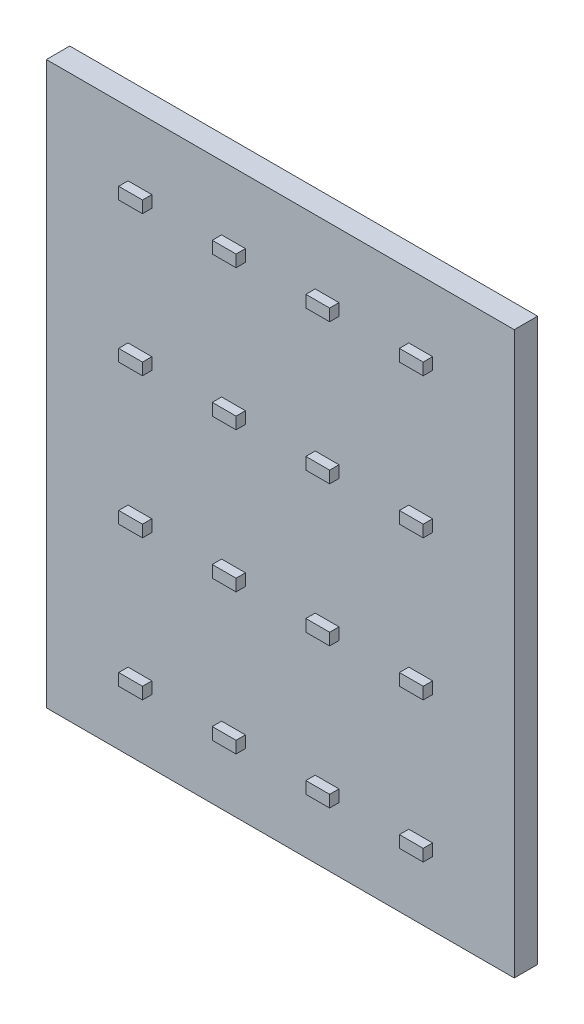
SolidWorks part; units mm, degrees
ref_plane "前视基准面" through (0, 0, 0) normal (0, 0, 1) x (1, 0, 0)
ref_plane "上视基准面" through (0, 0, 0) normal (0, 1, 0) x (1, 0, 0)
ref_plane "右视基准面" through (0, 0, 0) normal (1, 0, 0) x (0, 0, -1)
sketch "草图1" plane through (0, 0, 0) normal (0, 0, 1) x (1, 0, 0)
  line L1 (-50, 60) -> (50, 60)
  line L2 (-50, 60) -> (-50, -60)
  line L3 (-50, -60) -> (50, -60)
  line L4 (50, 60) -> (50, -60)
  line L5 (0, -60) -> (0, 60) construction
  line L6 (-50, 0) -> (50, 0) construction
  point P0 (0, 0)
  dimension "D1" = 120
  dimension "D2" = 100
extrude "凸台-拉伸1" add sketch "草图1" along normal blind 5
sketch "草图2" plane through (0, 0, 5) normal (0, 0, 1) x (1, 0, 0)
  line L0 (-12.543, 46.2715) -> (-12.543, 43.7285)
  line L1 (-32.543, 46.2715) -> (-27.457, 46.2715)
  line L2 (-32.543, 46.2715) -> (-32.543, 43.7285)
  line L3 (-32.543, 43.7285) -> (-27.457, 43.7285)
  line L4 (-27.457, 46.2715) -> (-27.457, 43.7285)
  line L5 (-30, 43.7285) -> (-30, 46.2715) construction
  line L6 (-32.543, 45) -> (-27.457, 45) construction
  line L11 (-12.543, 46.2715) -> (-7.457, 46.2715)
  line L12 (-7.457, 46.2715) -> (-7.457, 43.7285)
  line L17 (-12.543, 43.7285) -> (-7.457, 43.7285)
  line L18 (7.457, 46.2715) -> (7.457, 43.7285)
  line L19 (7.457, 46.2715) -> (12.543, 46.2715)
  line L20 (12.543, 46.2715) -> (12.543, 43.7285)
  line L21 (7.457, 43.7285) -> (12.543, 43.7285)
  line L22 (27.457, 46.2715) -> (27.457, 43.7285)
  line L23 (27.457, 46.2715) -> (32.543, 46.2715)
  line L24 (32.543, 46.2715) -> (32.543, 43.7285)
  line L25 (27.457, 43.7285) -> (32.543, 43.7285)
  line L26 (-32.543, 16.2715) -> (-32.543, 13.7285)
  line L27 (-32.543, 16.2715) -> (-27.457, 16.2715)
  line L28 (-27.457, 16.2715) -> (-27.457, 13.7285)
  line L29 (-32.543, 13.7285) -> (-27.457, 13.7285)
  line L30 (-12.543, 16.2715) -> (-12.543, 13.7285)
  line L31 (-12.543, 13.7285) -> (-7.457, 13.7285)
  line L32 (-7.457, 16.2715) -> (-7.457, 13.7285)
  line L33 (-12.543, 16.2715) -> (-7.457, 16.2715)
  line L34 (7.457, 16.2715) -> (7.457, 13.7285)
  line L35 (7.457, 13.7285) -> (12.543, 13.7285)
  line L36 (12.543, 16.2715) -> (12.543, 13.7285)
  line L37 (7.457, 16.2715) -> (12.543, 16.2715)
  line L38 (27.457, 16.2715) -> (27.457, 13.7285)
  line L39 (27.457, 13.7285) -> (32.543, 13.7285)
  line L40 (32.543, 16.2715) -> (32.543, 13.7285)
  line L41 (27.457, 16.2715) -> (32.543, 16.2715)
  line L42 (-32.543, -13.7285) -> (-32.543, -16.2715)
  line L43 (-32.543, -13.7285) -> (-27.457, -13.7285)
  line L44 (-27.457, -13.7285) -> (-27.457, -16.2715)
  line L45 (-32.543, -16.2715) -> (-27.457, -16.2715)
  line L46 (-12.543, -13.7285) -> (-12.543, -16.2715)
  line L47 (-12.543, -16.2715) -> (-7.457, -16.2715)
  line L48 (-7.457, -13.7285) -> (-7.457, -16.2715)
  line L49 (-12.543, -13.7285) -> (-7.457, -13.7285)
  line L50 (7.457, -13.7285) -> (7.457, -16.2715)
  line L51 (7.457, -16.2715) -> (12.543, -16.2715)
  line L52 (12.543, -13.7285) -> (12.543, -16.2715)
  line L53 (7.457, -13.7285) -> (12.543, -13.7285)
  line L54 (27.457, -13.7285) -> (27.457, -16.2715)
  line L55 (27.457, -16.2715) -> (32.543, -16.2715)
  line L56 (32.543, -13.7285) -> (32.543, -16.2715)
  line L57 (27.457, -13.7285) -> (32.543, -13.7285)
  line L58 (-32.543, -43.7285) -> (-32.543, -46.2715)
  line L59 (-32.543, -43.7285) -> (-27.457, -43.7285)
  line L60 (-27.457, -43.7285) -> (-27.457, -46.2715)
  line L61 (-32.543, -46.2715) -> (-27.457, -46.2715)
  line L62 (-12.543, -43.7285) -> (-12.543, -46.2715)
  line L63 (-12.543, -46.2715) -> (-7.457, -46.2715)
  line L64 (-7.457, -43.7285) -> (-7.457, -46.2715)
  line L65 (-12.543, -43.7285) -> (-7.457, -43.7285)
  line L66 (7.457, -43.7285) -> (7.457, -46.2715)
  line L67 (7.457, -46.2715) -> (12.543, -46.2715)
  line L68 (12.543, -43.7285) -> (12.543, -46.2715)
  line L69 (7.457, -43.7285) -> (12.543, -43.7285)
  line L70 (27.457, -43.7285) -> (27.457, -46.2715)
  line L71 (27.457, -46.2715) -> (32.543, -46.2715)
  line L72 (32.543, -43.7285) -> (32.543, -46.2715)
  line L73 (27.457, -43.7285) -> (32.543, -43.7285)
  point P0 (-30, 45)
  dimension "D1" = 30
  dimension "D2" = 45
  dimension "D3" = 4
  dimension "D4" = 4
extrude "凸台-拉伸2" add sketch "草图2" along normal blind 2
